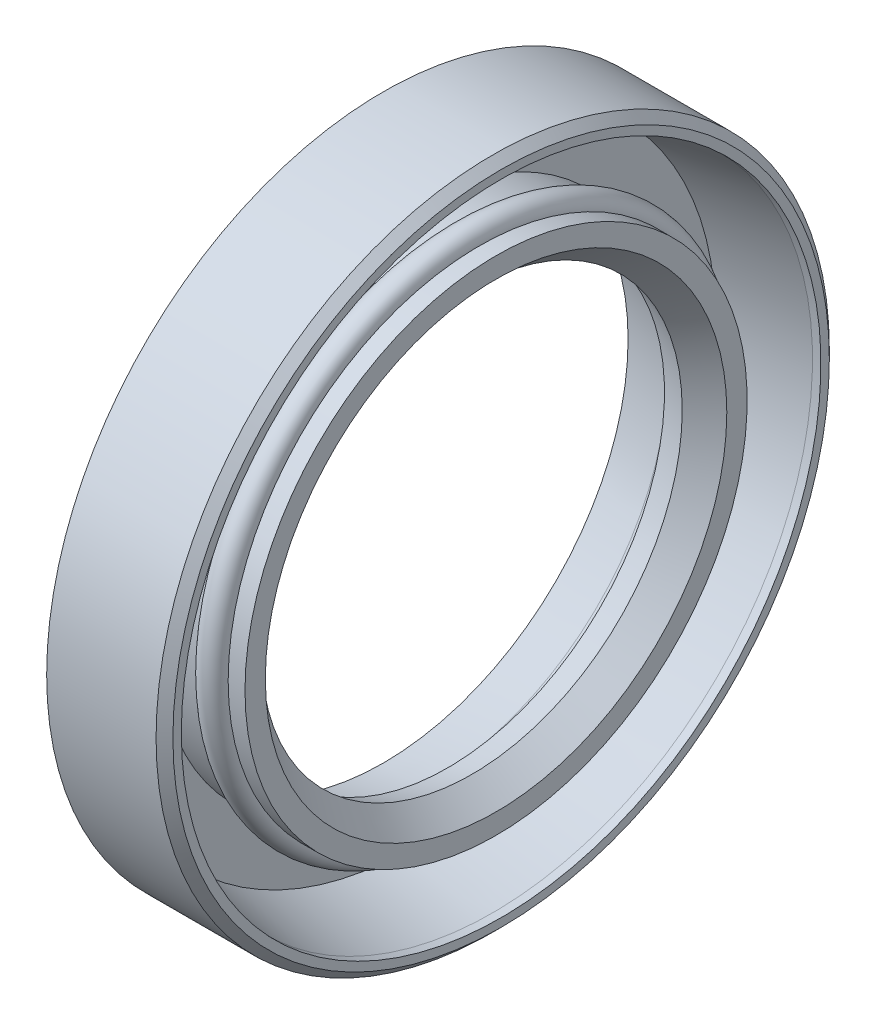
SolidWorks part; units mm, degrees
ref_plane "Front Plane" through (0, 0, 0) normal (0, 0, 1) x (1, 0, 0)
ref_plane "Top Plane" through (0, 0, 0) normal (0, 1, 0) x (1, 0, 0)
ref_plane "Right Plane" through (0, 0, 0) normal (1, 0, 0) x (0, 0, -1)
sketch "Sketch1" plane through (0, 0, 0) normal (0, 0, 1) x (1, 0, 0)
  line L0 (0, 20) -> (0, 14.5441)
  line L1 (0, 14.5441) -> (2.85, 14.0416)
  line L2 (3.8197, 12.8859) -> (5.2599, 12.5)
  line L4 (6.7, 14.9168) -> (5.7, 14.9168)
  line L5 (4.1, 14.9168) -> (1.6, 14.9168)
  line L6 (1.6, 14.9168) -> (1.6, 18.136)
  line L7 (1.6, 18.136) -> (6.5, 19)
  line L8 (6.5, 19) -> (7, 19)
  line L9 (7, 19) -> (7, 19.5)
  line L10 (6.5, 20) -> (0, 20)
  line L11 (7, 19.5) -> (6.5, 20)
  line L12 (5.2599, 12.5) -> (6.7, 13.7084)
  line L13 (6.7, 13.7084) -> (6.7, 14.9168)
  line L14 (3.8197, 12.8859) -> (3.8197, 12.5) construction
  line L15 (3.8197, 12.5) -> (5.2599, 12.5) construction
  line L16 (5.2599, 12.5) -> (6.7, 12.5) construction
  line L17 (6.7, 12.5) -> (6.7, 13.7084) construction
  line L18 (1.6, 14.9168) -> (2.85, 14.0416) construction
  line L19 (4.1, 14.9168) -> (2.85, 14.0416) construction
  line L20 (0, 0) -> (21.4535, 0) construction
  arc A0 (2.85, 14.0416) -> (3.8197, 12.8859) centre (2.6462, 12.8859) cw
  arc A1 (5.7, 14.9168) -> (4.1, 14.9168) centre (4.9, 14.9168) ccw
  circle A2 centre (4.9, 14.9168) radius 0.5
  point P17 (7, 20)
  dimension "D3" = 0.8
  dimension "D16" = 1
  dimension "D1" = 7
  dimension "D2" = 0.5
  dimension "D4" = 1
  dimension "D6" = 2.5
  dimension "D7" = 0.2
  dimension "D8" = 7.5
  dimension "D9" = 20
  dimension "D10" = 100
  dimension "D11" = 1
  dimension "D12" = 80
  dimension "D13" = 15
  dimension "D14" = 40
  dimension "D15" = 35
revolve "Revolve1" add sketch "Sketch1" angle 360 about L20
sketch "Sketch2" plane through (0, 0, 0) normal (-1, 0, 0) x (0, 0, 1)
  line L0 (0, 0) -> (0, 20) construction
  circle A0 centre (0, 0) radius 20 construction
